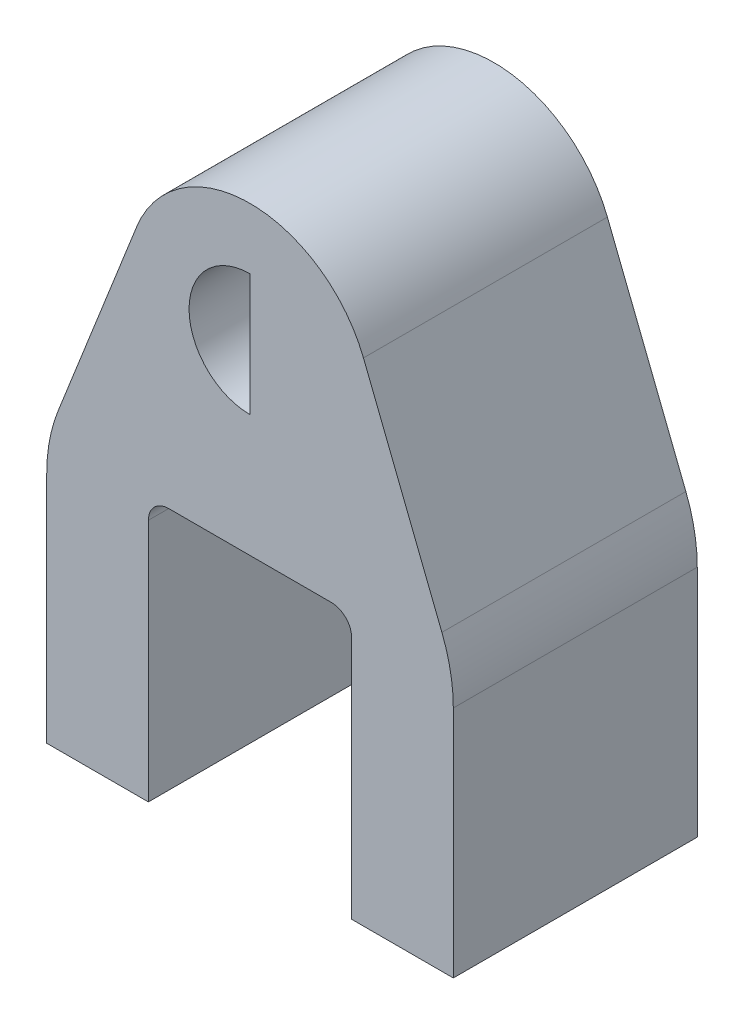
SolidWorks part; units mm, degrees
ref_plane "Front Plane" through (0, 0, 0) normal (0, 0, 1) x (1, 0, 0)
ref_plane "Top Plane" through (0, 0, 0) normal (0, 1, 0) x (1, 0, 0)
ref_plane "Right Plane" through (0, 0, 0) normal (1, 0, 0) x (0, 0, -1)
sketch "Sketch1" plane through (0, 0, 0) normal (0, 0, 1) x (1, 0, 0)
  line L0 (0, 0) -> (0, 53.0613) construction
  line L1 (12.7, 8.5287) -> (-12.7, 8.5287)
  line L2 (-15.875, 5.3537) -> (-15.875, -32.7463)
  line L3 (15.875, 5.3537) -> (15.875, -32.7463)
  line L4 (-15.875, -32.7463) -> (-31.75, -32.7463)
  line L5 (15.875, -32.7463) -> (31.75, -32.7463)
  line L6 (-31.75, -32.7463) -> (-31.75, 3.7749)
  line L7 (31.75, -32.7463) -> (31.75, 3.7749)
  line L8 (-29.9706, 13.1145) -> (-17.7154, 44.1085)
  line L9 (29.9706, 13.1145) -> (17.7154, 44.1085)
  arc A0 (-17.7154, 44.1085) -> (17.7154, 44.1085) centre (0, 37.1037) cw
  arc A1 (17.7154, 44.1085) -> (-17.7154, 44.1085) centre (0, 37.1037) ccw
  circle A2 centre (0, 37.1037) radius 9.525
  arc A3 (-31.75, 3.7749) -> (-29.9706, 13.1145) centre (-6.35, 3.7749) cw
  arc A4 (31.75, 3.7749) -> (29.9706, 13.1145) centre (6.35, 3.7749) ccw
  arc A5 (-12.7, 8.5287) -> (-15.875, 5.3537) centre (-12.7, 5.3537) ccw
  arc A6 (15.875, 5.3537) -> (12.7, 8.5287) centre (12.7, 5.3537) ccw
  point P14 (-15.875, -13.6963)
  point P15 (15.875, -13.6963)
  point P19 (0, 0)
  point P20 (0, 0)
  point P23 (0, 0)
  point P24 (0, 0)
  point P29 (0, 0)
  point P32 (18.7332, 45.406)
  point P33 (0, 0)
  point P34 (0, 0)
  point P35 (34.3647, 8.1754)
  point P36 (-31.75, -1.7528)
  point P37 (-31.3012, 8.5287)
  point P38 (0, 0)
  point P39 (0, 0)
  point P40 (31.3012, 8.5287)
  point P41 (15.875, 7.0249)
  point P42 (-31.75, 6.5236)
  point P43 (-31.75, 4.8526)
  dimension "D1" = 19.05
  dimension "D6" = 69.85
  dimension "D2" = 19.05
  dimension "D7" = 25.4
  dimension "D3" = 25.4
  dimension "D8" = 3.175
  dimension "D9" = 3.175
  dimension "D4" = 31.75
  dimension "D5" = 15.875
  dimension "D10" = 41.275
extrude "Boss-Extrude1" add sketch "Sketch1" along normal mid plane 38.1 contours L1 L0 A2 A0 L8 A3 L6 L4 L2 A5 | L0 L1 A6 L3 L5 L7 A4 L9 A1 A2
sketch "Sketch2" plane through (0, 0, 0) normal (1, 0, 0) x (0, 0, -1)
  line L0 (-19.05, -32.7463) -> (19.05, -32.7463) construction
  line L1 (0, -13.6963) -> (0, 16.2438) construction
  line L2 (-19.05, -13.6963) -> (-11.1125, 50.7777)
  line L3 (19.05, -13.6963) -> (11.1125, 50.7777)
  line L4 (-11.1125, 50.7777) -> (11.1125, 50.7777)
  arc A0 (-19.05, -13.6963) -> (19.05, -13.6963) centre (0, -13.6963) ccw
  point P1 (0, 0)
  point P10 (0, 50.7777)
  point P11 (0, 0)
  dimension "D1" = 19.05
  dimension "D2" = 22.225
